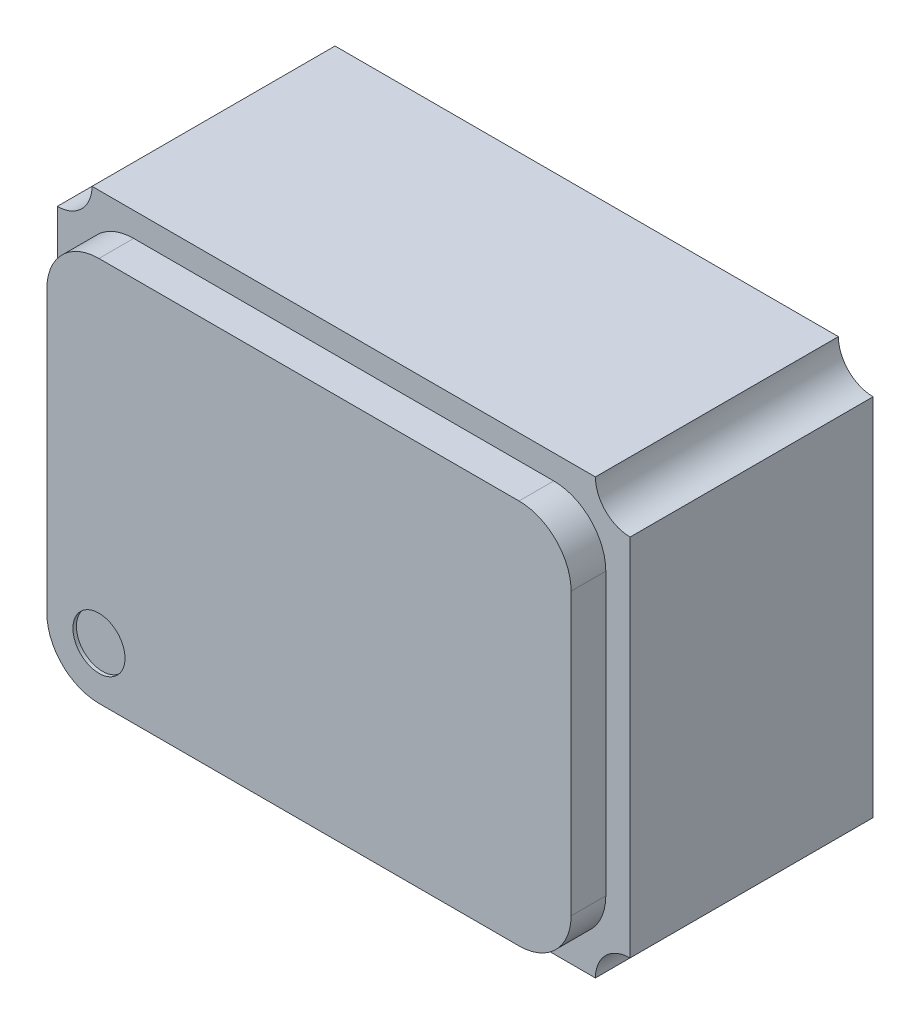
SolidWorks part; units mm, degrees
ref_plane "Front Plane" through (0, 0, 0) normal (0, 0, 1) x (1, 0, 0)
ref_plane "Top Plane" through (0, 0, 0) normal (0, 1, 0) x (1, 0, 0)
ref_plane "Right Plane" through (0, 0, 0) normal (1, 0, 0) x (0, 0, -1)
sketch "Sketch1" plane through (0, 0, 0) normal (0, 0, 1) x (1, 0, 0)
  line L1 (-0.825, 0.625) -> (0.825, 0.625)
  line L2 (-0.825, 0.625) -> (-0.825, -0.625)
  line L3 (-0.825, -0.625) -> (0.825, -0.625)
  line L4 (0.825, 0.625) -> (0.825, -0.625)
  line L5 (-0.825, 0.625) -> (0.825, -0.625) construction
  line L6 (-0.825, -0.625) -> (0.825, 0.625) construction
  point P0 (0, 0)
  dimension "D1" = 1.25
  dimension "D2" = 1.65
extrude "Boss-Extrude1" add sketch "Sketch1" along normal blind 0.7
sketch "Sketch2" plane through (0, 0, 0.7) normal (0, 0, 1) x (1, 0, 0)
  line L0 (0.825, -0.625) -> (0.825, 0.625) construction
  line L1 (-0.755, 0.555) -> (0.755, 0.555)
  line L2 (-0.755, 0.555) -> (-0.755, -0.555)
  line L3 (-0.755, -0.555) -> (0.755, -0.555)
  line L4 (0.755, 0.555) -> (0.755, -0.555)
  line L5 (-0.755, 0.555) -> (0.755, -0.555) construction
  line L6 (-0.755, -0.555) -> (0.755, 0.555) construction
  line L7 (0.825, 0.625) -> (-0.825, 0.625) construction
  point P0 (0, 0)
  dimension "D1" = 0.07
  dimension "D2" = 0.07
extrude "Boss-Extrude2" add sketch "Sketch2" along normal blind 0.1
fillet "Fillet1" radius 0.15 4 edges at (-0.755, 0.555, 0.75) (0.755, 0.555, 0.75) (0.755, -0.555, 0.75) (-0.755, -0.555, 0.75)
sketch "Sketch3" plane through (0, 0, 0.7) normal (0, 0, 1) x (1, 0, 0)
  circle A0 centre (-0.825, 0.625) radius 0.1
  circle A1 centre (0.825, 0.625) radius 0.1
  circle A2 centre (0.825, -0.625) radius 0.1
  circle A3 centre (-0.825, -0.625) radius 0.1
  dimension "D1" = 0.2
extrude "Cut-Extrude1" cut sketch "Sketch3" against normal through all
sketch "Sketch4" plane through (0, 0, 0.8) normal (0, 0, 1) x (1, 0, 0)
  circle A0 centre (-0.605, -0.405) radius 0.075
  dimension "D1" = 0.15
extrude "Cut-Extrude2" cut sketch "Sketch4" against normal blind 0.01
